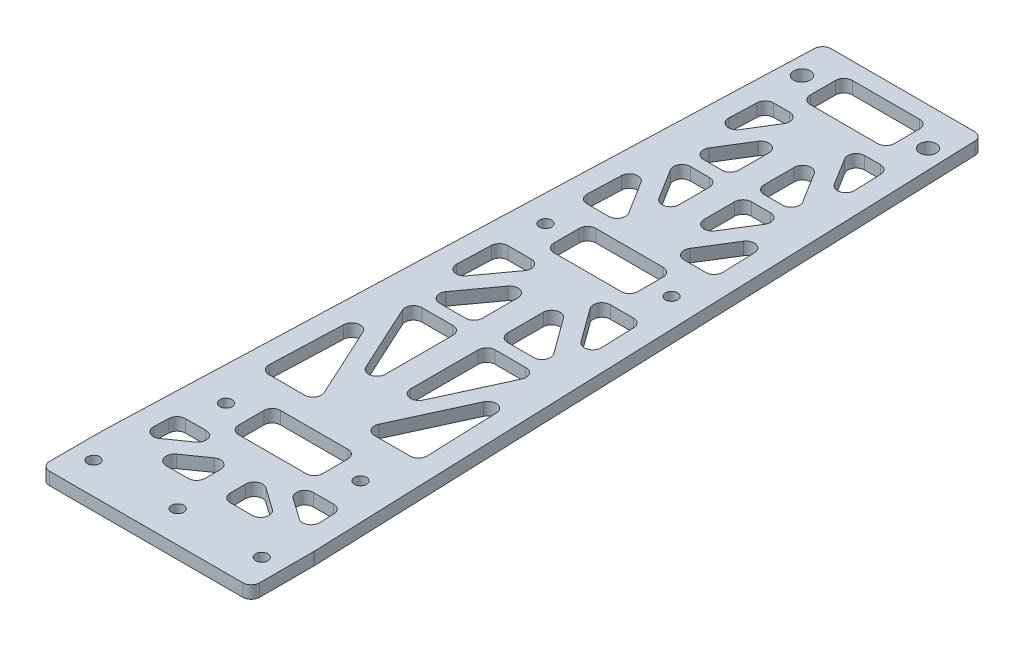
SolidWorks part; units mm, degrees
material "Thornel Mat VMA"
ref_plane "前视基准面" through (0, 0, 0) normal (0, 0, 1) x (1, 0, 0)
ref_plane "上视基准面" through (0, 0, 0) normal (0, 1, 0) x (1, 0, 0)
ref_plane "右视基准面" through (0, 0, 0) normal (1, 0, 0) x (0, 0, -1)
other "Configuration Table"
sketch "草图1" plane through (0, 0, 0) normal (0, 1, 0) x (1, 0, 0)
  line L0 (-25, 0) -> (-19, 0)
  line L1 (-19, 165) -> (19, 165)
  line L2 (-19, 165) -> (-19, 0)
  line L3 (-19, 0) -> (19, 0) construction
  line L4 (19, 165) -> (19, 0)
  line L5 (-25, 0) -> (25, 0) construction
  line L6 (-25, 0) -> (-25, -15)
  line L7 (-25, -15) -> (25, -15)
  line L8 (25, 0) -> (25, -15)
  line L9 (19, 0) -> (25, 0)
  line L10 (-19, 156) -> (19, 156) construction
  line L11 (-25, -7.5) -> (25, -7.5) construction
  circle A0 centre (0, -7.5) radius 1.45
  circle A1 centre (20, -7.5) radius 1.45
  circle A2 centre (-20, -7.5) radius 1.45
  circle A3 centre (-15, 156) radius 1.95
  circle A4 centre (15, 156) radius 1.95
  point P8 (22, 0)
  dimension "D7" = 2.9
  dimension "D8" = 2.9
  dimension "D9" = 2.9
  dimension "D12" = 3.9
  dimension "D13" = 3.9
  dimension "D1" = 15
  dimension "D2" = 38
  dimension "D3" = 50
  dimension "D4" = 25
  dimension "D5" = 165
  dimension "D6" = 156
  dimension "D10" = 20
  dimension "D11" = 20
  dimension "D14" = 15
  dimension "D15" = 30
extrude "凸台-拉伸1" add sketch "草图1" along normal blind 3
sketch "草图2" plane through (0, 3, 0) normal (0, 1, 0) x (1, 0, 0)
  line L0 (-19, 165) -> (-25, 0)
  line L1 (-25, 0) -> (-19, 0)
  line L2 (-19, 0) -> (-19, 165)
  line L3 (19, 165) -> (25, 0)
  line L4 (25, 0) -> (19, 0)
  line L5 (19, 0) -> (19, 165)
extrude "凸台-拉伸2" add sketch "草图2" against normal blind 3
fillet "圆角1" radius 2 6 edges at (19, 1.5, -165) (-19, 1.5, -165) (-25, 1.5, 0) (25, 1.5, 0) (25, 1.5, 15) (-25, 1.5, 15)
sketch "草图3" plane through (0, 3, 0) normal (0, 1, 0) x (1, 0, 0)
  line L0 (-16, 20) -> (16, 20) construction
  line L1 (0, 20) -> (0, 0) construction
  circle A0 centre (16, 20) radius 1.45
  circle A1 centre (-16, 20) radius 1.45
  dimension "D1" = 2.9
  dimension "D2" = 2.9
  dimension "D3" = 32
  dimension "D4" = 20
extrude "切除-拉伸1" cut sketch "草图3" against normal through all
sketch "草图4" plane through (0, 3, 0) normal (0, 1, 0) x (1, 0, 0)
  line L0 (0, 95) -> (0, 0) construction
  line L1 (-15, 95) -> (15, 95) construction
  circle A0 centre (-15, 95) radius 1.45
  circle A1 centre (15, 95) radius 1.45
  dimension "D2" = 2.9
  dimension "D3" = 2.9
  dimension "D1" = 95
  dimension "D4" = 30
extrude "切除-拉伸2" cut sketch "草图4" against normal through all
sketch "草图5" plane through (0, 3, 0) normal (0, 1, 0) x (1, 0, 0)
  line L0 (0, 0) -> (0, 165) construction
  line L1 (17.0714, 165) -> (-17.0714, 165) construction
  line L2 (-14.6512, 147) -> (14.6512, 147)
  line L3 (-14.6512, 147) -> (-19.9967, 0)
  line L4 (-19.9967, 0) -> (19.9967, 0)
  line L5 (-19.0701, 163.0727) -> (-24.9987, 0.0363) construction
  line L6 (-23, -15) -> (23, -15) construction
  line L7 (14.6512, 147) -> (19.9967, 0)
  line L8 (-15.3785, 127) -> (15.3785, 127)
  line L9 (-15.4876, 124) -> (15.4876, 124)
  line L10 (-16.2149, 104) -> (16.2149, 104)
  line L11 (-16.8694, 86) -> (16.8694, 86)
  line L12 (-17.5967, 66) -> (17.5967, 66)
  line L13 (-17.7058, 63) -> (17.7058, 63)
  line L14 (-18.8694, 31) -> (18.8694, 31)
  line L15 (-19.5603, 12) -> (19.5603, 12)
  point P15 (0, 0)
  point P16 (0, 147)
  dimension "D1" = 5
  dimension "D2" = 15
  dimension "D3" = 18
  dimension "D4" = 20
  dimension "D5" = 3
  dimension "D6" = 20
  dimension "D7" = 18
  dimension "D8" = 20
  dimension "D9" = 3
  dimension "D10" = 32
  dimension "D11" = 12
extrude "切除-拉伸3" cut sketch "草图5" against normal through all contours L8 L0 L2 L3 | L0 L8 L7 L2 | L10 L0 L9 L3 | L0 L10 L7 L9 | L12 L0 L11 L3 | L0 L12 L7 L11 | L14 L0 L13 L3 | L0 L14 L7 L13 | L4 L0 L15 L3 | L0 L4 L7 L15
sketch "草图6" plane through (0, 3, 0) normal (0, 1, 0) x (1, 0, 0)
  line L0 (0, 0) -> (0, 147) construction
  line L1 (-14.6512, 147) -> (14.6512, 147) construction
  line L2 (3, 0) -> (3, 147)
  line L3 (-3, 0) -> (-3, 147)
  line L4 (-3, 147) -> (3, 147)
  line L5 (-3, 0) -> (3, 0)
  dimension "D1" = 3
  dimension "D2" = 3
extrude "凸台-拉伸3" add sketch "草图6" against normal blind 3
sketch "草图9" plane through (0, 3, 0) normal (0, 1, 0) x (1, 0, 0)
  line L0 (-3, 147) -> (-15.3785, 127)
  line L1 (-15.4876, 124) -> (-3, 104)
  line L2 (3, 147) -> (15.3785, 127)
  line L3 (15.4876, 124) -> (3, 104)
  line L4 (-3, 86) -> (-17.5967, 66)
  line L5 (-17.7058, 63) -> (-3, 31)
  line L6 (3, 86) -> (17.5967, 66)
  line L7 (17.7058, 63) -> (3, 31)
  line L8 (-3, 12) -> (-19.9967, 0)
  line L9 (3, 12) -> (19.9967, 0)
  line L10 (-4.7006, 148.0526) -> (-17.0791, 128.0526)
  line L11 (-17.1841, 122.9408) -> (-4.6965, 102.9408)
  line L12 (1.2994, 145.9474) -> (13.6779, 125.9474)
  line L13 (13.7911, 125.0592) -> (1.3035, 105.0592)
  line L14 (-4.6155, 87.179) -> (-19.2122, 67.179)
  line L15 (-19.5231, 62.1649) -> (-4.8173, 30.1649)
  line L16 (1.3845, 84.821) -> (15.9812, 64.821)
  line L17 (15.8885, 63.8351) -> (1.1827, 31.8351)
  line L18 (-4.1535, 13.6338) -> (-21.1502, 1.6338)
  line L19 (1.8465, 10.3662) -> (18.8432, -1.6338)
  line L20 (-1.2994, 145.9474) -> (-13.6779, 125.9474)
  line L21 (-13.7911, 125.0592) -> (-1.3035, 105.0592)
  line L22 (4.7006, 148.0526) -> (17.0791, 128.0526)
  line L23 (17.1841, 122.9408) -> (4.6965, 102.9408)
  line L24 (-1.3845, 84.821) -> (-15.9812, 64.821)
  line L25 (-15.8885, 63.8351) -> (-1.1827, 31.8351)
  line L26 (4.6155, 87.179) -> (19.2122, 67.179)
  line L27 (19.5231, 62.1649) -> (4.8173, 30.1649)
  line L28 (-1.8465, 10.3662) -> (-18.8432, -1.6338)
  line L29 (4.1535, 13.6338) -> (21.1502, 1.6338)
  line L34 (-3, 127) -> (-3, 147)
  line L35 (-15.3785, 127) -> (-3, 127)
  line L36 (-14.6512, 147) -> (-15.3785, 127)
  line L37 (-3, 147) -> (-14.6512, 147)
  line L38 (-3, 127) -> (-3, 147)
  line L39 (-15.3785, 127) -> (-3, 127)
  line L40 (-14.6512, 147) -> (-15.3785, 127)
  line L41 (-3, 147) -> (-14.6512, 147)
  line L42 (3, 0) -> (19.9967, 0)
  line L43 (3, 12) -> (3, 0)
  line L44 (19.5603, 12) -> (3, 12)
  line L45 (19.9967, 0) -> (19.5603, 12)
  line L46 (3, 0) -> (19.9967, 0)
  line L47 (3, 12) -> (3, 0)
  line L48 (19.5603, 12) -> (3, 12)
  line L49 (19.9967, 0) -> (19.5603, 12)
  line L50 (3, 127) -> (15.3785, 127)
  line L51 (3, 147) -> (3, 127)
  line L52 (14.6512, 147) -> (3, 147)
  line L53 (15.3785, 127) -> (14.6512, 147)
  line L54 (3, 127) -> (15.3785, 127)
  line L55 (3, 147) -> (3, 127)
  line L56 (14.6512, 147) -> (3, 147)
  line L57 (15.3785, 127) -> (14.6512, 147)
  line L58 (3, 104) -> (16.2149, 104)
  line L59 (3, 124) -> (3, 104)
  line L60 (15.4876, 124) -> (3, 124)
  line L61 (16.2149, 104) -> (15.4876, 124)
  line L62 (3, 104) -> (16.2149, 104)
  line L63 (3, 124) -> (3, 104)
  line L64 (15.4876, 124) -> (3, 124)
  line L65 (16.2149, 104) -> (15.4876, 124)
  line L66 (3, 66) -> (17.5967, 66)
  line L67 (3, 86) -> (3, 66)
  line L68 (16.8694, 86) -> (3, 86)
  line L69 (17.5967, 66) -> (16.8694, 86)
  line L70 (3, 66) -> (17.5967, 66)
  line L71 (3, 86) -> (3, 66)
  line L72 (16.8694, 86) -> (3, 86)
  line L73 (17.5967, 66) -> (16.8694, 86)
  line L74 (3, 31) -> (18.8694, 31)
  line L75 (3, 63) -> (3, 31)
  line L76 (17.7058, 63) -> (3, 63)
  line L77 (18.8694, 31) -> (17.7058, 63)
  line L78 (3, 31) -> (18.8694, 31)
  line L79 (3, 63) -> (3, 31)
  line L80 (17.7058, 63) -> (3, 63)
  line L81 (18.8694, 31) -> (17.7058, 63)
  line L82 (-3, 12) -> (-19.5603, 12)
  line L83 (-3, 0) -> (-3, 12)
  line L84 (-19.9967, 0) -> (-3, 0)
  line L85 (-19.5603, 12) -> (-19.9967, 0)
  line L86 (-3, 12) -> (-19.5603, 12)
  line L87 (-3, 0) -> (-3, 12)
  line L88 (-19.9967, 0) -> (-3, 0)
  line L89 (-19.5603, 12) -> (-19.9967, 0)
  line L90 (-3, 63) -> (-17.7058, 63)
  line L91 (-3, 31) -> (-3, 63)
  line L92 (-18.8694, 31) -> (-3, 31)
  line L93 (-17.7058, 63) -> (-18.8694, 31)
  line L94 (-3, 63) -> (-17.7058, 63)
  line L95 (-3, 31) -> (-3, 63)
  line L96 (-18.8694, 31) -> (-3, 31)
  line L97 (-17.7058, 63) -> (-18.8694, 31)
  line L98 (-3, 86) -> (-16.8694, 86)
  line L99 (-3, 66) -> (-3, 86)
  line L100 (-17.5967, 66) -> (-3, 66)
  line L101 (-16.8694, 86) -> (-17.5967, 66)
  line L102 (-3, 86) -> (-16.8694, 86)
  line L103 (-3, 66) -> (-3, 86)
  line L104 (-17.5967, 66) -> (-3, 66)
  line L105 (-16.8694, 86) -> (-17.5967, 66)
  line L106 (-3, 124) -> (-15.4876, 124)
  line L107 (-3, 104) -> (-3, 124)
  line L108 (-16.2149, 104) -> (-3, 104)
  line L109 (-15.4876, 124) -> (-16.2149, 104)
  line L110 (-3, 124) -> (-15.4876, 124)
  line L111 (-3, 104) -> (-3, 124)
  line L112 (-16.2149, 104) -> (-3, 104)
  line L113 (-15.4876, 124) -> (-16.2149, 104)
  circle A1 centre (-15, 95) radius 1.45
  circle A2 centre (-15, 95) radius 1.45
  circle A3 centre (15, 95) radius 1.45
  circle A4 centre (15, 95) radius 1.45
  circle A5 centre (16, 20) radius 1.45
  circle A6 centre (16, 20) radius 1.45
  circle A7 centre (-16, 20) radius 1.45
  circle A8 centre (-16, 20) radius 1.45
  circle A9 centre (-15, 156) radius 1.95
  circle A10 centre (-15, 156) radius 1.95
  circle A11 centre (20, -7.5) radius 1.45
  circle A12 centre (20, -7.5) radius 1.45
  circle A13 centre (0, -7.5) radius 1.45
  circle A14 centre (0, -7.5) radius 1.45
  circle A15 centre (-20, -7.5) radius 1.45
  circle A16 centre (-20, -7.5) radius 1.45
  circle A17 centre (15, 156) radius 1.95
  circle A18 centre (15, 156) radius 1.95
  dimension "D1" = 2
  dimension "D3" = 0
  dimension "D2" = 2
  dimension "D4" = 0
  dimension "D5" = 0
  dimension "D6" = 0
  dimension "D7" = 0
  dimension "D8" = 0
  dimension "D9" = 0
  dimension "D10" = 0
  dimension "D11" = 0
  dimension "D12" = 0
  dimension "D13" = 0
  dimension "D14" = 0
  dimension "D15" = 0
  dimension "D16" = 0
  dimension "D17" = 0
  dimension "D18" = 0
  dimension "D19" = 0
  dimension "D20" = 0
  dimension "D21" = 0
extrude "凸台-拉伸6" add sketch "草图9" against normal blind 3 contours L0 L41 L10 L40 | L0 L39 L20 L38 | L2 L55 L12 L54 | L2 L57 L22 L56 | L1 L113 L11 L112 | L1 L111 L21 L110 | L23 L65 L3 L62 | L3 L64 L13 L63 | L4 L104 L24 L103 | L14 L105 L4 L102 | L6 L71 L16 L70 | L6 L73 L26 L72 | L5 L95 L25 L94 | L5 L97 L15 L96 | L7 L80 L17 L79 | L27 L81 L7 L78 | L18 L89 L8 L86 | L8 L88 L28 L87 | L9 L49 L29 L48 | L9 L47 L19 L46
fillet "圆角2" radius 2 60 edges at (-3, 1.5, -127) (19.5603, 1.5, -12) (3, 1.5, 0) (14.6512, 1.5, -147) (3, 1.5, -127) (3, 1.5, -124) (16.2149, 1.5, -104) (16.8694, 1.5, -86) (3, 1.5, -66) (3, 1.5, -63) (18.8694, 1.5, -31) (-3, 1.5, 0) (-19.5603, 1.5, -12) (-18.8694, 1.5, -31) (-3, 1.5, -63) (-3, 1.5, -66) (-16.8694, 1.5, -86) (-16.2149, 1.5, -104) (-3, 1.5, -124) (-14.6512, 1.5, -147) (3, 1.5, -9.5518) (16.529, 1.5, 0) (3, 1.5, -143.1997) (13.0264, 1.5, -127) (3, 1.5, -82.6074) (15.1207, 1.5, -66) (15.2317, 1.5, -131.0375) (5.3521, 1.5, -147) (3, 1.5, -107.7763) (13.1298, 1.5, -124) (-5.3578, 1.5, -104) (-15.6174, 1.5, -120.4315) (15.6174, 1.5, -120.4315) (5.3578, 1.5, -104) (17.4669, 1.5, -69.5705) (5.476, 1.5, -86) (3, 1.5, -35.7896) (15.5047, 1.5, -63) (-5.2011, 1.5, -31) (-17.8672, 1.5, -58.5616) (17.8672, 1.5, -58.5616) (5.2011, 1.5, -31) (19.9053, 1.5, -2.5127) (6.4677, 1.5, -12) (-3, 1.5, -143.1997) (-13.0264, 1.5, -127) (-15.2317, 1.5, -131.0375) (-17.4669, 1.5, -69.5705) (-5.476, 1.5, -86) (-3, 1.5, -82.6074) (-15.1207, 1.5, -66) (-3, 1.5, -107.7763) (-13.1298, 1.5, -124) (-3, 1.5, -9.5518) (-16.529, 1.5, 0) (-19.9053, 1.5, -2.5127) (-6.4677, 1.5, -12) (-3, 1.5, -35.7896) (-15.5047, 1.5, -63) (-5.3521, 1.5, -147)
sketch "草图7" plane through (0, 3, 0) normal (0, 1, 0) x (1, 0, 0)
  line L0 (0, 165) -> (0, 0) construction
  line L1 (-10, 151) -> (10, 151)
  line L2 (-10, 151) -> (-10, 161)
  line L3 (-10, 161) -> (10, 161)
  line L4 (10, 151) -> (10, 161)
  line L5 (-10, 151) -> (10, 161) construction
  line L6 (-10, 161) -> (10, 151) construction
  line L7 (-10, 90) -> (10, 90)
  line L8 (-10, 90) -> (-10, 100)
  line L9 (-10, 100) -> (10, 100)
  line L10 (10, 90) -> (10, 100)
  line L11 (-10, 90) -> (10, 100) construction
  line L12 (-10, 100) -> (10, 90) construction
  line L13 (-10, 15) -> (10, 15)
  line L14 (-10, 15) -> (-10, 25)
  line L15 (-10, 25) -> (10, 25)
  line L16 (10, 15) -> (10, 25)
  line L17 (-10, 15) -> (10, 25) construction
  line L18 (-10, 25) -> (10, 15) construction
  line L19 (17.0714, 165) -> (-17.0714, 165) construction
  line L20 (-15, 156) -> (15, 156) construction
  line L21 (-15, 95) -> (15, 95) construction
  line L22 (-16, 20) -> (16, 20) construction
  point P0 (0, 156)
  point P5 (0, 95)
  point P10 (0, 20)
  point P20 (0, 20)
  point P21 (0, 20)
  dimension "D1" = 10
  dimension "D2" = 20
  dimension "D3" = 10
  dimension "D4" = 20
  dimension "D5" = 10
  dimension "D6" = 20
extrude "切除-拉伸4" cut sketch "草图7" against normal through all
fillet "圆角3" radius 2 12 edges at (-10, 1.5, -15) (-10, 1.5, -25) (10, 1.5, -25) (10, 1.5, -15) (-10, 1.5, -90) (-10, 1.5, -100) (10, 1.5, -100) (10, 1.5, -90) (-10, 1.5, -151) (10, 1.5, -161) (10, 1.5, -151) (-10, 1.5, -161)
